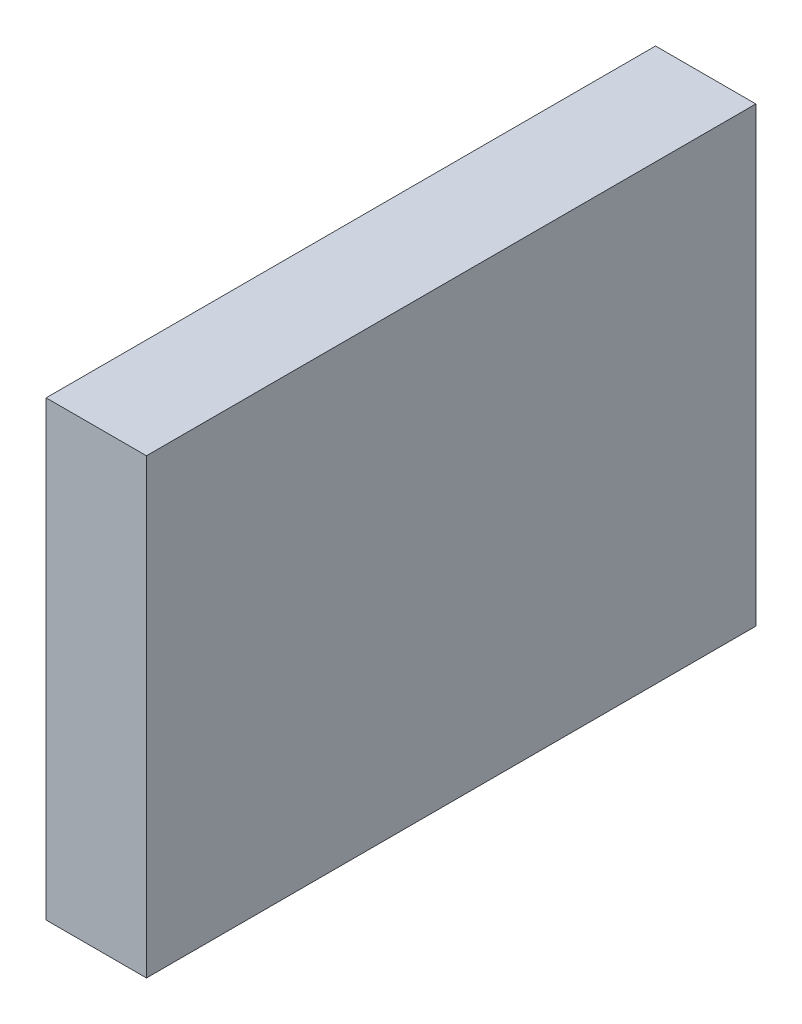
SolidWorks part; units mm, degrees
ref_plane "Alzado" through (0, 0, 0) normal (0, 0, 1) x (1, 0, 0)
ref_plane "Planta" through (0, 0, 0) normal (0, 1, 0) x (1, 0, 0)
ref_plane "Vista lateral" through (0, 0, 0) normal (1, 0, 0) x (0, 0, -1)
sketch "Croquis1" plane through (0, 0, 0) normal (1, 0, 0) x (0, 0, -1)
  line L1 (-185.3678, 127.2644) -> (45.4372, 127.2644)
  line L2 (-185.3678, 127.2644) -> (-185.3678, -44.0299)
  line L3 (-185.3678, -44.0299) -> (45.4372, -44.0299)
  line L4 (45.4372, 127.2644) -> (45.4372, -44.0299)
  line L5 (-185.3678, 127.2644) -> (45.4372, -44.0299) construction
  line L6 (-185.3678, -44.0299) -> (45.4372, 127.2644) construction
  point P0 (-69.9653, 41.6173)
extrude "Saliente-Extruir1" add sketch "Croquis1" along normal blind 38
